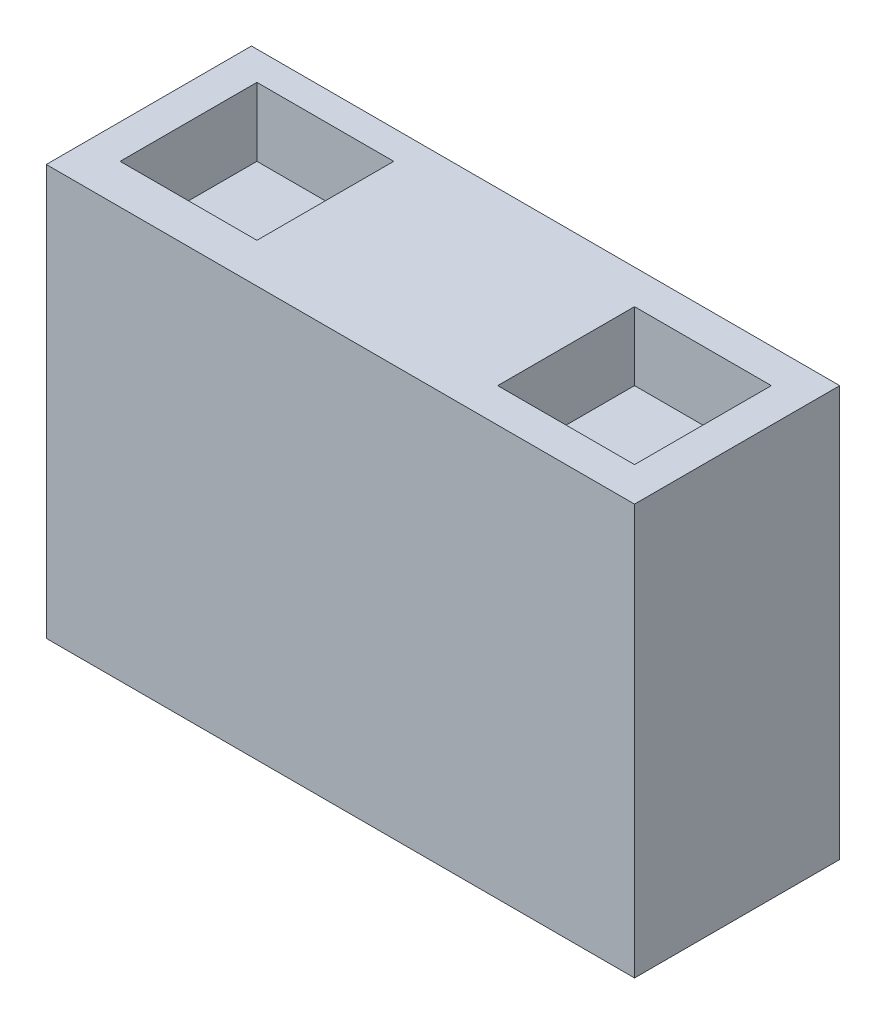
SolidWorks part; units mm, degrees
ref_plane "Front Plane" through (0, 0, 0) normal (0, 0, 1) x (1, 0, 0)
ref_plane "Top Plane" through (0, 0, 0) normal (0, 1, 0) x (1, 0, 0)
ref_plane "Right Plane" through (0, 0, 0) normal (1, 0, 0) x (0, 0, -1)
sketch "Sketch1" plane through (0, 0, 0) normal (0, 0, 1) x (1, 0, 0)
  line L1 (-14.2686, 13.7583) -> (28.7314, 13.7583)
  line L2 (-14.2686, 13.7583) -> (-14.2686, -16.2417)
  line L3 (-14.2686, -16.2417) -> (28.7314, -16.2417)
  line L4 (28.7314, 13.7583) -> (28.7314, -16.2417)
  dimension "D1" = 30
  dimension "D2" = 43
extrude "Boss-Extrude1" add sketch "Sketch1" along normal blind 15
sketch "Sketch2" plane through (0, 13.7583, 0) normal (0, 1, 0) x (1, 0, 0)
  line L0 (-14.2686, -15) -> (-14.2686, 0) construction
  line L1 (-11.7686, -2.1017) -> (-1.7686, -2.1017)
  line L2 (-11.7686, -2.1017) -> (-11.7686, -12.1017)
  line L3 (-11.7686, -12.1017) -> (-1.7686, -12.1017)
  line L4 (-1.7686, -2.1017) -> (-1.7686, -12.1017)
  line L5 (16.2314, -2.5) -> (26.2314, -2.5)
  line L6 (16.2314, -2.5) -> (16.2314, -12.5)
  line L7 (16.2314, -12.5) -> (26.2314, -12.5)
  line L8 (26.2314, -2.5) -> (26.2314, -12.5)
  line L9 (28.7314, -15) -> (-14.2686, -15) construction
  line L10 (28.7314, -15) -> (28.7314, 0) construction
  dimension "D1" = 10
  dimension "D2" = 10
  dimension "D3" = 10
  dimension "D4" = 10
  dimension "D5" = 2.5
  dimension "D6" = 2.8983
  dimension "D7" = 2.5
  dimension "D8" = 2.5
extrude "Cut-Extrude1" cut sketch "Sketch2" against normal blind 5
